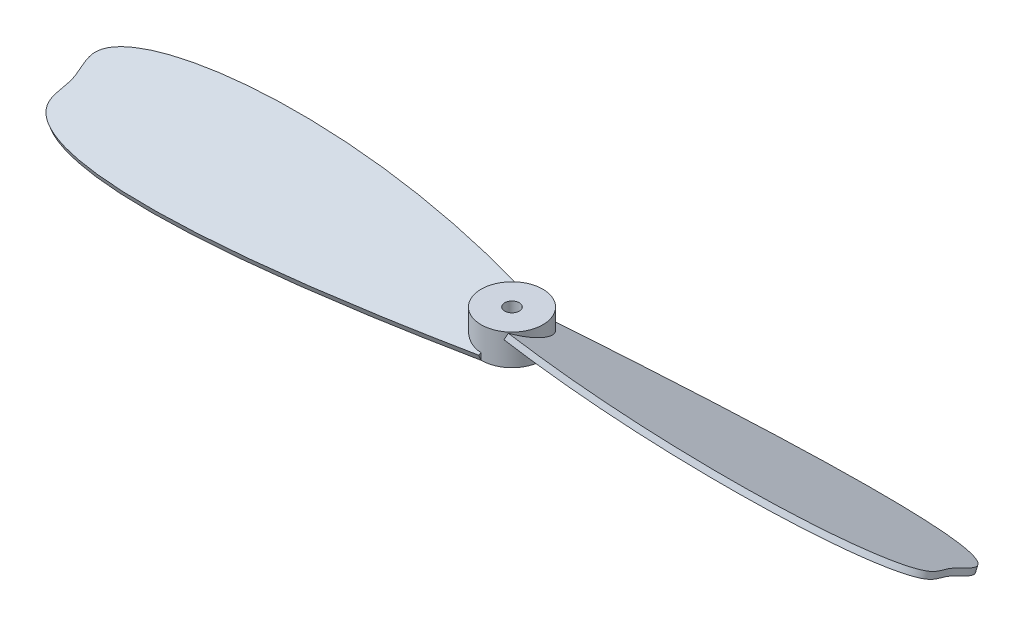
SolidWorks part; units mm, degrees
material "ABS"
ref_plane "Front Plane" through (0, 0, 0) normal (0, 0, 1) x (1, 0, 0)
ref_plane "Top Plane" through (0, 0, 0) normal (0, 1, 0) x (1, 0, 0)
ref_plane "Right Plane" through (0, 0, 0) normal (1, 0, 0) x (0, 0, -1)
sketch "Sketch1" plane through (0, 0, 0) normal (0, 1, 0) x (1, 0, 0)
  circle A0 centre (0, 0) radius 6.35
  circle A1 centre (0, 0) radius 88.9
  circle A2 centre (0, 0) radius 1.5
extrude "Boss-Extrude1" add sketch "Sketch1" along normal blind 6.35 contours A0 A2
sketch "Sketch2" plane through (0, 0, 0) normal (0, -1, 0) x (1, 0, 0)
  line L0 (0, -6.35) -> (88.9, -6.35) construction
  line L1 (0, 6.35) -> (88.9, 6.35) construction
  line L2 (0, 0) -> (88.9, 0) construction
  circle A0 centre (0, 0) radius 6.35 construction
ref_plane "Plane1" through (0, 2.2839, -0.9695) normal (0, 0.9205, -0.3907) x (-1, 0, 0)
sketch "Sketch5" plane through (0, 2.2839, -0.9695) normal (0, 0.9205, -0.3907) x (-1, 0, 0)
  line L0 (0, -5.8452) -> (0, 5.8452)
  spline S0 degree 3 poles (0, 5.8452) (-43.2367, 17.0996) (-94.2907, 12.9517) (-88.0617, -0.0094) (-92.6162, -10.411) (-66.8219, -15.4764) (0, -5.8452) knots 0 0 0 0 0.469262 0.561899 0.654536 1 1 1 1
extrude "Boss-Extrude2" add sketch "Sketch5" along normal blind 1.27
sketch "Sketch6" plane through (0, 0, 0) normal (0, -1, 0) x (1, 0, 0)
  circle A0 centre (0, 0) radius 1.5
pattern_circular "CirPattern1" count 2 over 360 about axis through (0, 6.35, 0) along (0, 1, 0) of "Boss-Extrude2"
extrude "Cut-Extrude7" cut sketch "Sketch6" against normal through all
